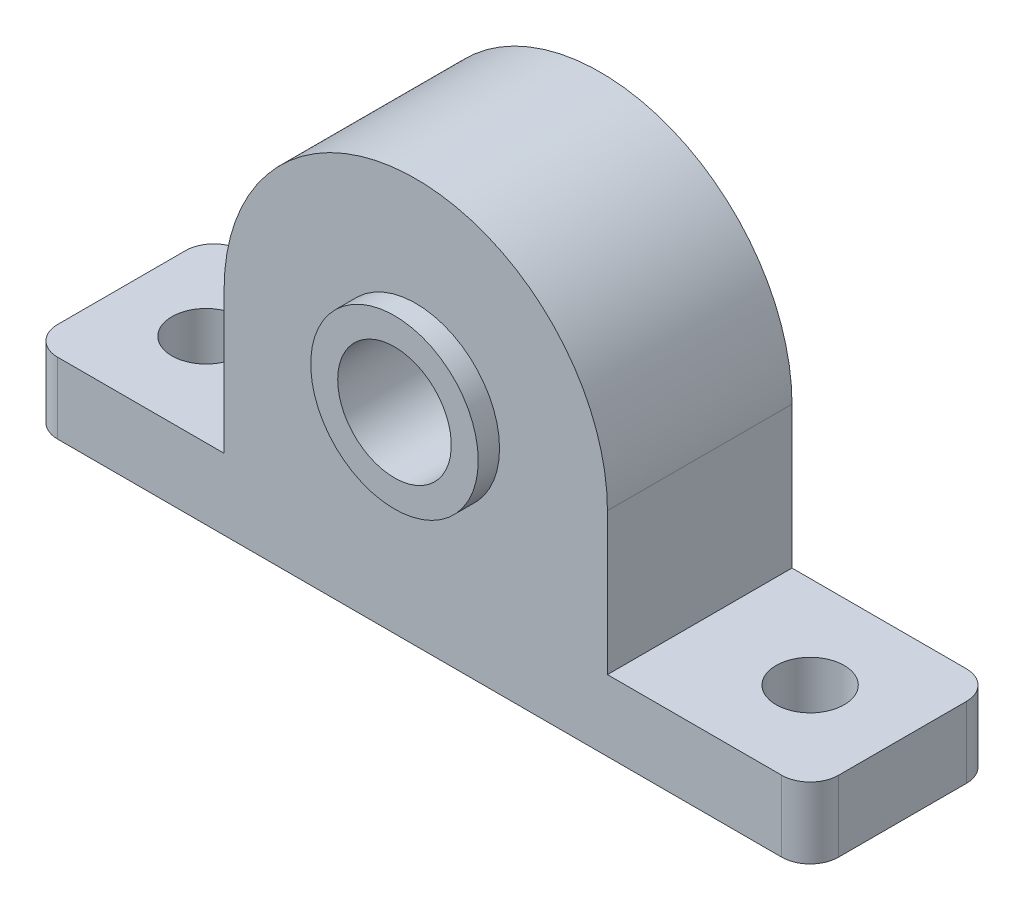
SolidWorks part; units mm, degrees
ref_plane "Front Plane" through (0, 0, 0) normal (0, 0, 1) x (1, 0, 0)
ref_plane "Top Plane" through (0, 0, 0) normal (0, 1, 0) x (1, 0, 0)
ref_plane "Right Plane" through (0, 0, 0) normal (1, 0, 0) x (0, 0, -1)
sketch "Sketch2" plane through (0, 0, 0) normal (0, 0, 1) x (1, 0, 0)
  line L0 (0, 0) -> (55, 0)
  line L1 (55, 0) -> (55, 5)
  line L2 (40.7222, 5) -> (55, 5)
  line L3 (0, 0) -> (0, 5)
  line L4 (0, 5) -> (13.7222, 5)
  line L5 (40.7222, 15) -> (40.7222, 5)
  line L6 (13.7222, 15) -> (13.7222, 5)
  arc A0 (40.7222, 15) -> (13.7222, 15) centre (27.2222, 15) ccw
  circle A1 centre (27.2222, 15) radius 4
  dimension "D5" = 27
  dimension "D4" = 8
  dimension "D1" = 55
  dimension "D2" = 5
  dimension "D3" = 5
extrude "Boss-Extrude1" add sketch "Sketch2" along normal blind 13
sketch "Sketch3" plane through (0, 0, 13) normal (0, 0, 1) x (1, 0, 0)
  circle A0 centre (27.2222, 15) radius 4
  circle A1 centre (27.2222, 15) radius 5.9
  dimension "D1" = 11.8
  dimension "D2" = 8
extrude "Boss-Extrude2" add sketch "Sketch3" along normal blind 1.5
sketch "Sketch4" plane through (0, 5, 0) normal (0, 1, 0) x (1, 0, 0)
  circle A0 centre (48.5, -6.5) radius 2.4
  circle A1 centre (5.9444, -6.5) radius 2.4
  point P0 (0, 0)
  dimension "D2" = 4.8
extrude "Cut-Extrude1" cut sketch "Sketch4" against normal blind 5
fillet "Fillet1" radius 2 1 edges at (55, 2.5, 13)
fillet "Fillet2" radius 2 3 edges at (0, 2.5, 13) (0, 2.5, 0) (55, 2.5, 0)
